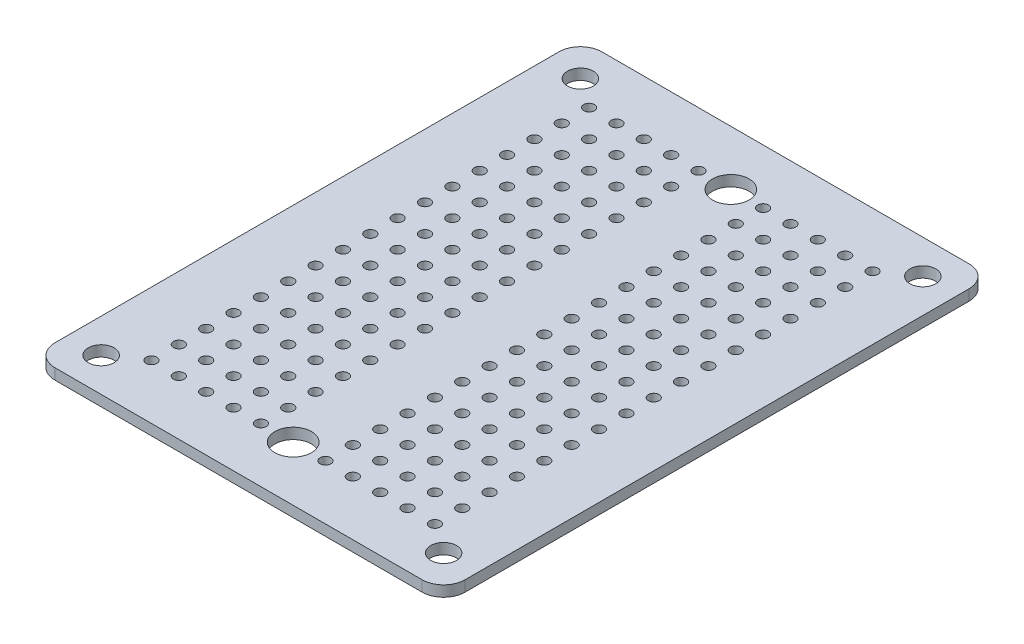
SolidWorks part; units mm, degrees
ref_plane "Front Plane" through (0, 0, 0) normal (0, 0, 1) x (1, 0, 0)
ref_plane "Top Plane" through (0, 0, 0) normal (0, 1, 0) x (1, 0, 0)
ref_plane "Right Plane" through (0, 0, 0) normal (1, 0, 0) x (0, 0, -1)
sketch "Sketch2" plane through (0, 0, 0) normal (0, 1, 0) x (1, 0, 0)
  line L1 (-19.05, -25.4) -> (19.05, -25.4)
  line L2 (-19.05, -25.4) -> (-19.05, 25.4)
  line L3 (-19.05, 25.4) -> (19.05, 25.4)
  line L4 (19.05, -25.4) -> (19.05, 25.4)
  line L5 (-19.05, -25.4) -> (19.05, 25.4) construction
  line L6 (-19.05, 25.4) -> (19.05, -25.4) construction
  point P0 (0, 0)
  dimension "D1" = 38.1
  dimension "D2" = 50.8
extrude "Boss-Extrude1" add sketch "Sketch2" along normal mid plane 1
hole_wizard "M2 Clearance Hole1" positions "Sketch3" profile "Sketch4" hole size "M2" standard "ANSI Metric" end condition up to next
sketch "Sketch3" plane through (0, 0.5, 0) normal (0, 1, 0) x (1, 0, 0)
  line L1 (-15.9, -22.25) -> (15.9, -22.25)
  line L2 (-15.9, -22.25) -> (-15.9, 22.25)
  line L3 (-15.9, 22.25) -> (15.9, 22.25)
  line L4 (15.9, -22.25) -> (15.9, 22.25)
  line L5 (-15.9, -22.25) -> (15.9, 22.25) construction
  line L6 (-15.9, 22.25) -> (15.9, -22.25) construction
  point P2 (15.9, 22.25)
  point P233 (-15.9, -22.25)
  point P234 (-15.9, 22.25)
  point P235 (15.9, -22.25)
  point P247 (0, 0)
  point P248 (0, 0)
  dimension "D1" = 44.5
  dimension "D2" = 31.8
sketch "Sketch4" plane through (15.9, 0.5, -22.25) normal (1, 0, 0) x (0, 0, 1)
  line L0 (0, 0) -> (0, 1)
  line L1 (0, 1) -> (1.2, 1)
  line L2 (1.2, 1) -> (1.2, 0)
  line L5 (1.2, 0) -> (0, 0)
  line L11 (0, -6.35) -> (0, 107.95) construction
  dimension "Thru Hole Dia." = 2.4
  dimension "Thru Hole Depth" = 1
hole_wizard "M3 Clearance Hole1" positions "Sketch5" profile "Sketch6" hole size "M3" standard "ANSI Metric" end condition up to next
sketch "Sketch5" plane through (0, 0.5, 0) normal (0, 1, 0) x (1, 0, 0)
  line L0 (0, 20.32) -> (0, -20.32) construction
  point P1 (0, 20.32)
  point P2 (0, -20.32)
  point P5 (0, 0)
  dimension "D1" = 40.64
sketch "Sketch6" plane through (0, 0.5, -20.32) normal (1, 0, 0) x (0, 0, 1)
  line L0 (0, 0) -> (0, 1)
  line L1 (0, 1) -> (1.7, 1)
  line L2 (1.7, 1) -> (1.7, 0)
  line L5 (1.7, 0) -> (0, 0)
  line L11 (0, -6.35) -> (0, 107.95) construction
  dimension "Thru Hole Dia." = 3.4
  dimension "Thru Hole Depth" = 1
fillet "Fillet2" radius 2 4 edges at (-19.05, 0, 25.4) (19.05, 0, 25.4) (19.05, 0, -25.4) (-19.05, 0, -25.4)
sketch "Sketch7" plane through (0, 0.5, 0) normal (0, 1, 0) x (1, 0, 0)
  circle A0 centre (-3, 20.32) radius 0.5
  point P2 (-3.1338, 20.32)
  point P4 (-3.3132, 20.32)
  dimension "D1" = 1
  dimension "D2" = 3
extrude "Cut-Extrude1" cut sketch "Sketch7" against normal through all both and the other way through all
pattern_linear "LPattern1" count 5 spacing 2.54 along (-1, 0, 0) count 17 spacing 2.54 along (0, 0, 1) of "Cut-Extrude1"
mirror "Mirror1" about plane through (0, 0, 0) normal (1, 0, 0) of "LPattern1", "Cut-Extrude1"
